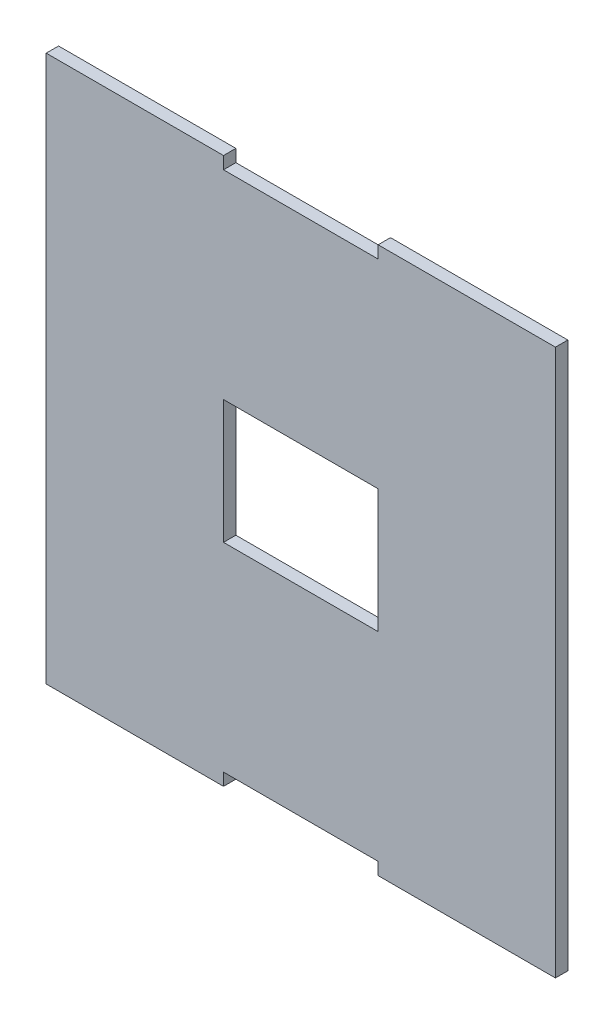
SolidWorks part; units mm, degrees
material "Carvalho"
ref_plane "Plano frontal" through (0, 0, 0) normal (0, 0, 1) x (1, 0, 0)
ref_plane "Plano superior" through (0, 0, 0) normal (0, 1, 0) x (1, 0, 0)
ref_plane "Plano direito" through (0, 0, 0) normal (1, 0, 0) x (0, 0, -1)
sketch "Esboço1" plane through (0, 0, 0) normal (0, 0, 1) x (1, 0, 0)
  line L0 (161, 0) -> (247, 0)
  line L1 (0, 0) -> (86, 0)
  line L2 (0, 0) -> (0, 265)
  line L3 (0, 265) -> (86, 265)
  line L4 (247, 0) -> (247, 265)
  line L6 (86, 0) -> (86, 6)
  line L7 (86, 6) -> (161, 6)
  line L8 (161, 0) -> (161, 6)
  line L11 (86, 265) -> (86, 259)
  line L12 (86, 259) -> (161, 259)
  line L13 (161, 265) -> (161, 259)
  line L14 (161, 265) -> (247, 265)
  line L16 (86, 102.5) -> (161, 102.5)
  line L17 (86, 102.5) -> (86, 162.5)
  line L18 (86, 162.5) -> (161, 162.5)
  line L19 (161, 102.5) -> (161, 162.5)
  dimension "D1" = 247
  dimension "D2" = 265
  dimension "D3" = 75
  dimension "D4" = 86
  dimension "D5" = 6
  dimension "D6" = 86
  dimension "D7" = 60
  dimension "D8" = 75
  dimension "D9" = 102.5
  dimension "D10" = 86
extrude "Ressalto-extrusão1" add sketch "Esboço1" along normal blind 6
